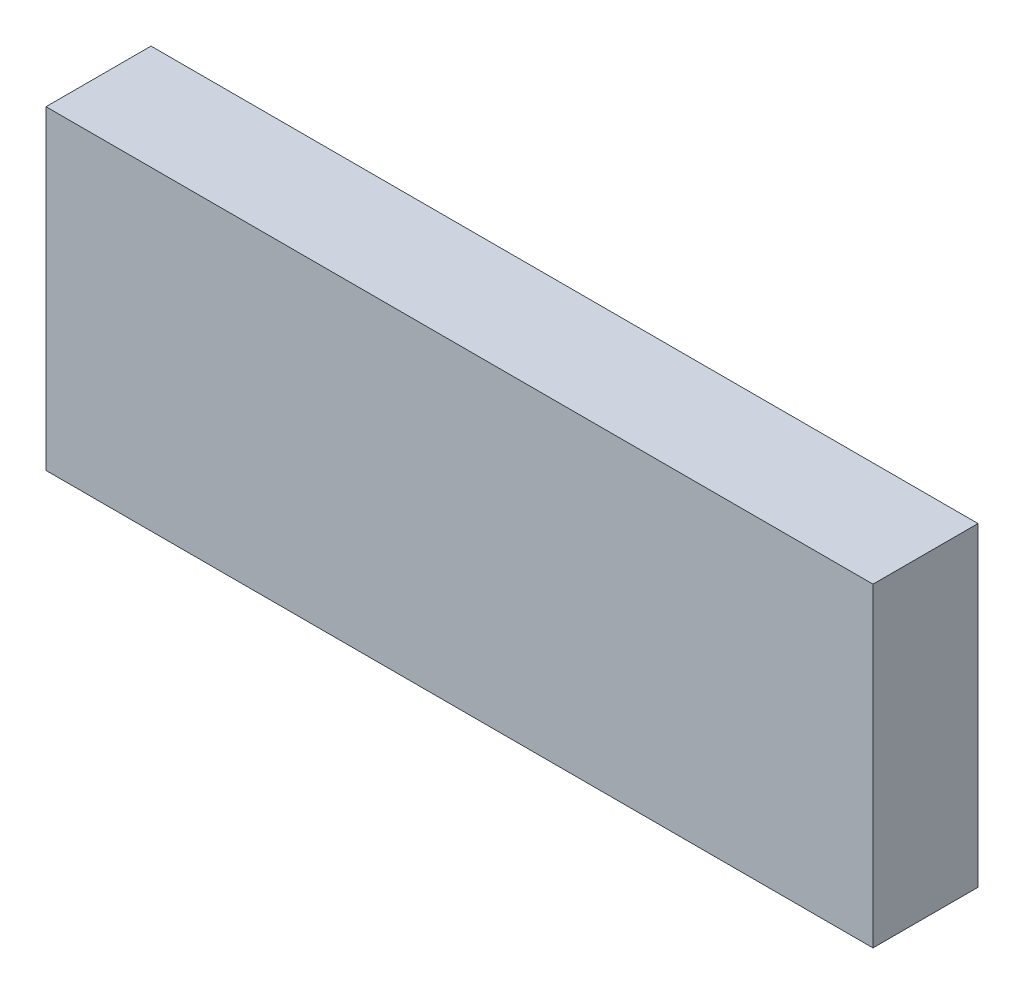
SolidWorks part; units mm, degrees
material "ABS"
ref_plane "Alzado" through (0, 0, 0) normal (0, 0, 1) x (1, 0, 0)
ref_plane "Planta" through (0, 0, 0) normal (0, 1, 0) x (1, 0, 0)
ref_plane "Vista lateral" through (0, 0, 0) normal (1, 0, 0) x (0, 0, -1)
sketch "Sketch1" plane through (0, 0, 0) normal (1, 0, 0) x (0, 0, -1)
  line L1 (-10, -30) -> (10, -30)
  line L2 (-10, -30) -> (-10, 30)
  line L3 (-10, 30) -> (10, 30)
  line L4 (10, -30) -> (10, 30)
  line L5 (-10, -30) -> (10, 30) construction
  line L6 (-10, 30) -> (10, -30) construction
  point P0 (0, 0)
  dimension "D1" = 20
  dimension "D2" = 60
extrude "Boss-Extrude1" add sketch "Sketch1" along normal blind 157.5
